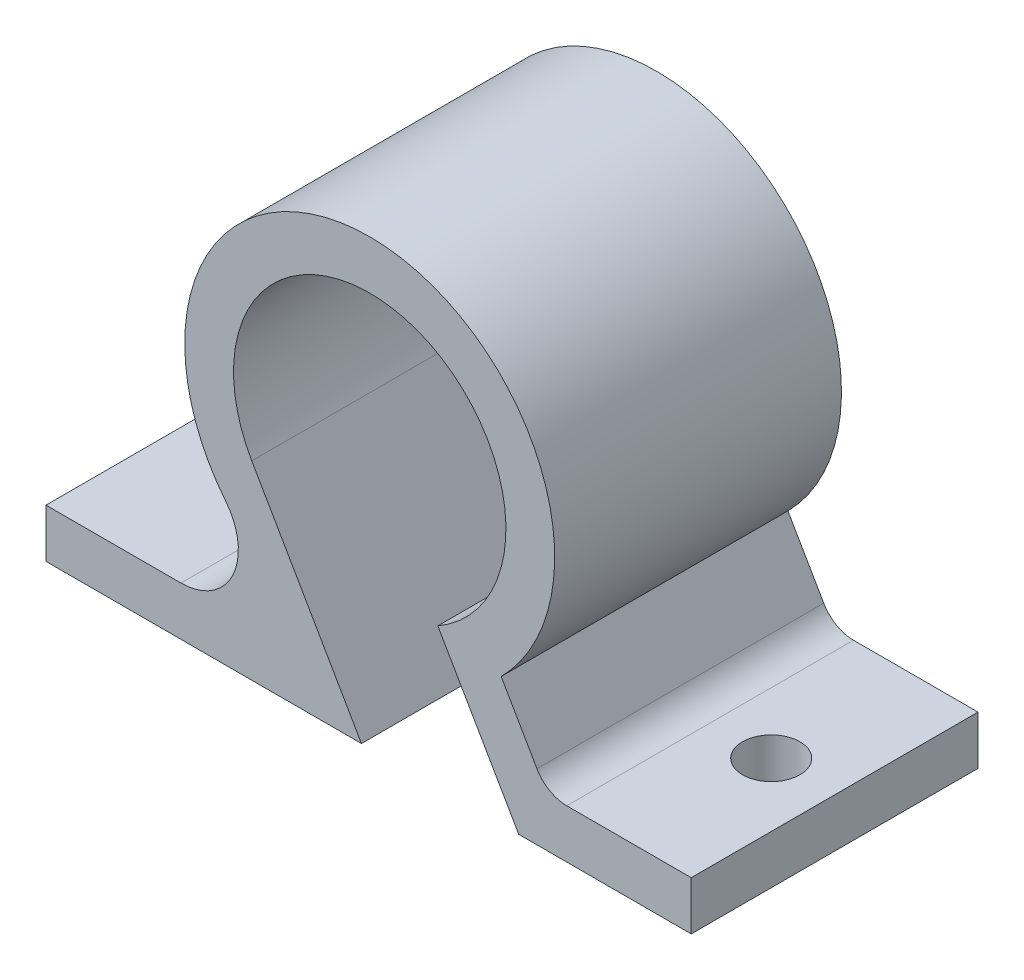
SolidWorks part; units mm, degrees
ref_plane "Front Plane" through (0, 0, 0) normal (0, 0, 1) x (1, 0, 0)
ref_plane "Top Plane" through (0, 0, 0) normal (0, 1, 0) x (1, 0, 0)
ref_plane "Right Plane" through (0, 0, 0) normal (1, 0, 0) x (0, 0, -1)
sketch "Sketch1" plane through (0, 0, 0) normal (0, 0, 1) x (1, 0, 0)
  line L0 (-65.8122, -73) -> (-112.8868, -73)
  line L1 (-112.8868, -73) -> (-112.8868, -90)
  line L2 (-112.8868, -90) -> (-2.8868, -90)
  line L3 (112.1132, -90) -> (112.1132, -73)
  line L4 (112.1132, -73) -> (68.7047, -73)
  line L5 (58.3124, -67) -> (45.8321, -45.3836)
  line L6 (23.75, -41.1362) -> (51.9615, -90)
  line L7 (-41.1362, -23.75) -> (-2.8868, -90)
  line L8 (23.75, -41.1362) -> (0, 0) construction
  line L9 (51.9615, -90) -> (112.1132, -90)
  arc A0 (23.75, -41.1362) -> (-41.1362, -23.75) centre (0, 0) ccw
  arc A1 (45.8321, -45.3836) -> (-50.2354, -40.4556) centre (0, 0) ccw
  arc A2 (-50.2354, -40.4556) -> (-65.8122, -73) centre (-65.8122, -53) cw
  arc A3 (68.7047, -73) -> (58.3124, -67) centre (68.7047, -61) cw
  point P19 (108.0344, -65.9353)
  dimension "D1" = 60
  dimension "D4" = 20
  dimension "D7" = 12
  dimension "D8" = 95
  dimension "D9" = 129
  dimension "D2" = 225
  dimension "D3" = 110
  dimension "D5" = 17
  dimension "D6" = 17
  dimension "D10" = 90
extrude "Boss-Extrude1" add sketch "Sketch1" along normal mid plane 100
sketch "Sketch2" plane through (0, -90, 0) normal (0, -1, 0) x (1, 0, 0)
  line L0 (0, 8.4296) -> (0, -3.1804) construction
  circle A0 centre (90, 0) radius 10
  circle A1 centre (-90, 0) radius 10
  point P5 (0, 0)
  dimension "D1" = 20
  dimension "D2" = 90
extrude "Cut-Extrude1" cut sketch "Sketch2" against normal up to next
